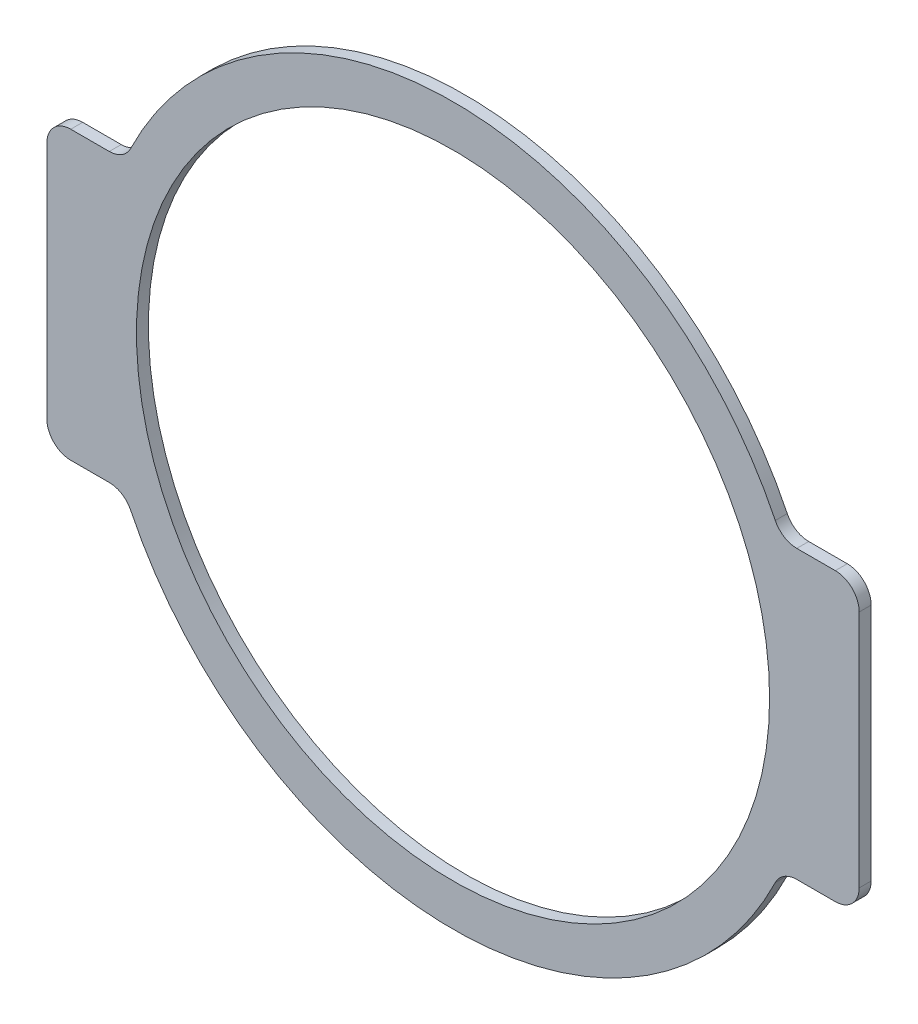
SolidWorks part; units mm, degrees
ref_plane "前视基准面" through (0, 0, 0) normal (0, 0, 1) x (1, 0, 0)
ref_plane "上视基准面" through (0, 0, 0) normal (0, 1, 0) x (1, 0, 0)
ref_plane "右视基准面" through (0, 0, 0) normal (1, 0, 0) x (0, 0, -1)
sketch "草图1" plane through (0, 0, 0) normal (0, 0, 1) x (1, 0, 0)
  line L6 (-170, 50) -> (-170, -50)
  line L7 (-160, -60) -> (-143.8749, -60)
  line L8 (143.8749, -60) -> (160, -60)
  line L9 (170, -50) -> (170, 50)
  line L10 (160, 60) -> (143.8749, 60)
  line L11 (-143.8749, 60) -> (-160, 60)
  line L12 (-170, 50) -> (-170, -50)
  line L13 (-160, -60) -> (-143.8749, -60)
  line L14 (143.8749, -60) -> (160, -60)
  line L15 (170, -50) -> (170, 50)
  line L16 (160, 60) -> (143.8749, 60)
  line L17 (-143.8749, 60) -> (-160, 60)
  arc A1 (0, -132.5) -> (0, 132.5) centre (0, 0) ccw construction
  arc A2 (0, 132.5) -> (0, -132.5) centre (0, 0) ccw construction
  arc A3 (0, -132.5) -> (0, 132.5) centre (0, 0) ccw
  arc A4 (0, 132.5) -> (0, -132.5) centre (0, 0) ccw
  arc A11 (-170, -50) -> (-160, -60) centre (-160, -50) ccw
  arc A12 (-134.8828, -65.625) -> (-143.8749, -60) centre (-143.8749, -70) ccw
  arc A13 (-134.8828, -65.625) -> (0, -150) centre (0, 0) ccw
  arc A14 (0, -150) -> (134.8828, -65.625) centre (0, 0) ccw
  arc A15 (143.8749, -60) -> (134.8828, -65.625) centre (143.8749, -70) ccw
  arc A16 (160, -60) -> (170, -50) centre (160, -50) ccw
  arc A17 (170, 50) -> (160, 60) centre (160, 50) ccw
  arc A18 (134.8828, 65.625) -> (143.8749, 60) centre (143.8749, 70) ccw
  arc A19 (134.8828, 65.625) -> (-134.8828, 65.625) centre (0, 0) ccw
  arc A20 (-143.8749, 60) -> (-134.8828, 65.625) centre (-143.8749, 70) ccw
  arc A21 (-160, 60) -> (-170, 50) centre (-160, 50) ccw
  arc A22 (-170, -50) -> (-160, -60) centre (-160, -50) ccw
  arc A23 (-134.8828, -65.625) -> (-143.8749, -60) centre (-143.8749, -70) ccw
  arc A24 (-134.8828, -65.625) -> (0, -150) centre (0, 0) ccw
  arc A25 (0, -150) -> (134.8828, -65.625) centre (0, 0) ccw
  arc A26 (143.8749, -60) -> (134.8828, -65.625) centre (143.8749, -70) ccw
  arc A27 (160, -60) -> (170, -50) centre (160, -50) ccw
  arc A28 (170, 50) -> (160, 60) centre (160, 50) ccw
  arc A29 (134.8828, 65.625) -> (143.8749, 60) centre (143.8749, 70) ccw
  arc A30 (134.8828, 65.625) -> (-134.8828, 65.625) centre (0, 0) ccw
  arc A31 (-143.8749, 60) -> (-134.8828, 65.625) centre (-143.8749, 70) ccw
  arc A32 (-160, 60) -> (-170, 50) centre (-160, 50) ccw
  dimension "D1" = 0
extrude "凸台-拉伸2" add sketch "草图1" along normal blind 5
